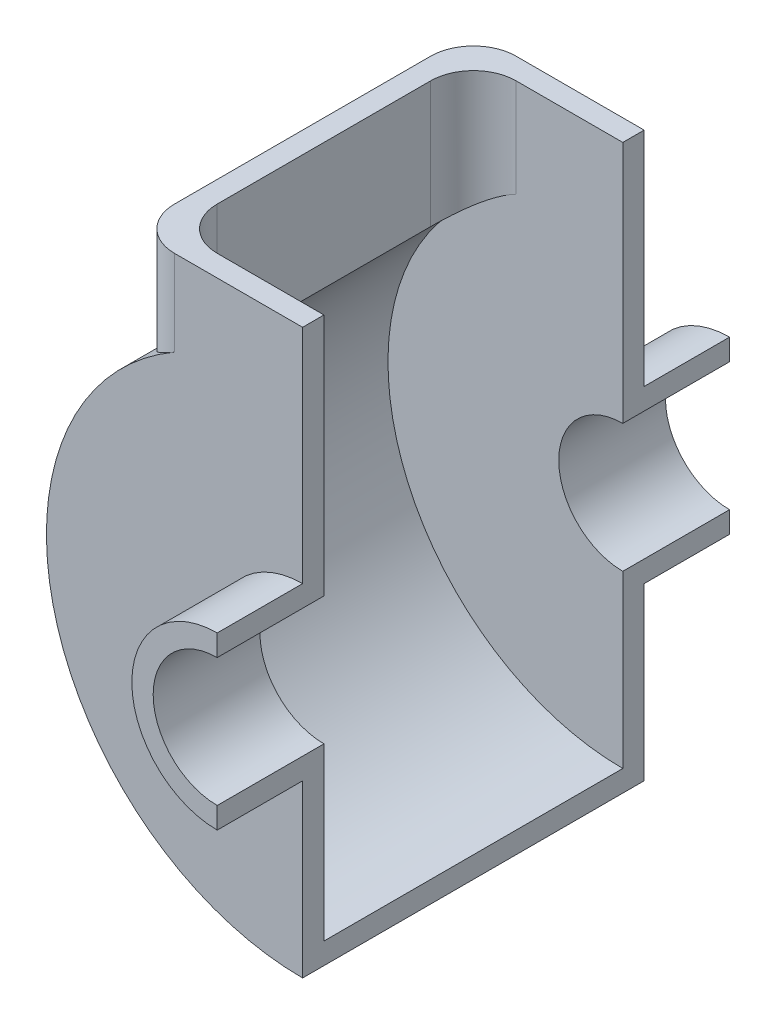
SolidWorks part; units mm, degrees
ref_plane "Płaszczyzna przednia" through (0, 0, 0) normal (0, 0, 1) x (1, 0, 0)
ref_plane "Płaszczyzna górna" through (0, 0, 0) normal (0, 1, 0) x (1, 0, 0)
ref_plane "Płaszczyzna prawa" through (0, 0, 0) normal (1, 0, 0) x (0, 0, -1)
sketch "Szkic1" plane through (0, 0, 0) normal (0, 0, 1) x (1, 0, 0)
  line L0 (0, -15) -> (0, -20)
  line L1 (0, 15) -> (0, 20)
  arc A0 (0, 20) -> (0, -20) centre (0, 0) ccw
  arc A1 (0, 15) -> (0, -15) centre (0, 0) ccw
  point P7 (-15, 0)
  point P8 (-20, 0)
  dimension "D1" = 20
  dimension "D2" = 15
extrude "Dodanie-wyciągnięcie1" add sketch "Szkic1" along normal blind 25 contours A0 L0 A1 L1
sketch "Szkic2" plane through (0, 0, 0) normal (0, 0, 1) x (1, 0, 0)
  line L0 (0, 20) -> (0, 72)
  line L1 (0, 72) -> (-40, 72)
  line L2 (-40, 72) -> (-40, 44.7214)
  line L3 (0, -20) -> (0, -60)
  arc A1 (0, 20) -> (0, -20) centre (0, 0) ccw
  arc A2 (0, 20) -> (0, -20) centre (0, 0) ccw construction
  arc A3 (0, -60) -> (-40, 44.7214) centre (0, 0) cw
  dimension "D1" = 52
  dimension "D3" = 60
  dimension "D2" = 40
extrude "Dodanie-wyciągnięcie2" add sketch "Szkic2" along normal blind 5 contours L2 A3 L3 A1 L0 L1
ref_plane "Płaszczyzna1" through (0, 0, -35) normal (0, 0, 1) x (1, 0, 0)
mirror "Lustro2" about plane through (0, 0, -35) normal (0, 0, 1) of bodies 102
sketch "Szkic3" plane through (0, 0, 0) normal (0, 0, -1) x (-1, 0, 0)
  line L0 (40, 72) -> (40, 44.7214) construction
  line L1 (40, 72) -> (40, 44.7214)
  arc A0 (0, -60) -> (40, 44.7214) centre (0, 0) ccw construction
  arc A1 (0, -60) -> (40, 44.7214) centre (0, 0) ccw
extrude "Wyciągnięcie-cienka ścianka7" add sketch "Szkic3" along normal up to next thin
fillet "Zaokrąglenie1" radius 10 4 edges at (-40, 58.3607, -75) (-40, 58.3607, 5) (-35, 57.2132, 0) (-35, 57.2132, -70)
